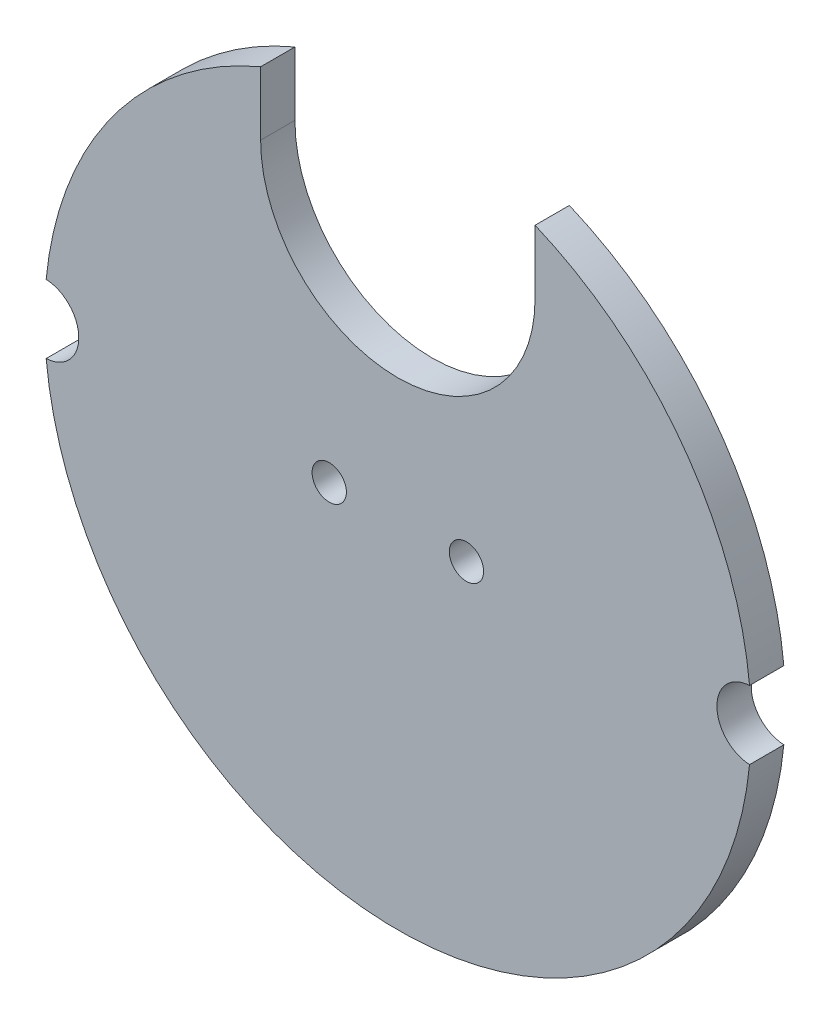
SolidWorks part; units mm, degrees
material "PC High Viscosity"
ref_plane "Front Plane" through (0, 0, 0) normal (0, 0, 1) x (1, 0, 0)
ref_plane "Top Plane" through (0, 0, 0) normal (0, 1, 0) x (1, 0, 0)
ref_plane "Right Plane" through (0, 0, 0) normal (1, 0, 0) x (0, 0, -1)
sketch "Sketch1" plane through (0, 0, 0) normal (0, 0, 1) x (1, 0, 0)
  circle A0 centre (0, 0) radius 65.405
  dimension "D1" = 130.81
extrude "Extrude1" add sketch "Sketch1" along normal blind 6.35
sketch "Sketch2" plane through (0, 0, 6.35) normal (0, 0, 1) x (1, 0, 0)
  line L0 (0, 65.405) -> (0, 48.5098) construction
  line L1 (-25.4, 48.5098) -> (-25.4, 60.2715)
  line L2 (-25.4, 60.2715) -> (-25.4, 72.0274)
  line L3 (-25.4, 72.0274) -> (25.4, 72.0274)
  line L4 (25.4, 72.0274) -> (25.4, 60.2715)
  line L5 (25.4, 60.2715) -> (25.4, 48.5098)
  line L6 (0, 0) -> (12.7, 0) construction
  line L7 (0, 0) -> (-12.7, 0) construction
  circle A0 centre (0, 0) radius 65.405 construction
  arc A1 (25.4, 48.5098) -> (-25.4, 48.5098) centre (0, 48.5098) cw
  circle A2 centre (-65.405, 0) radius 6.35
  circle A3 centre (65.405, 0) radius 6.35
  circle A4 centre (12.7, 0) radius 3.175
  circle A5 centre (-12.7, 0) radius 3.175
  dimension "D1" = 25.4
  dimension "D2" = 12.7
  dimension "D3" = 6.35
  dimension "D4" = 12.7
extrude "Extrude2" cut sketch "Sketch2" against normal through all
